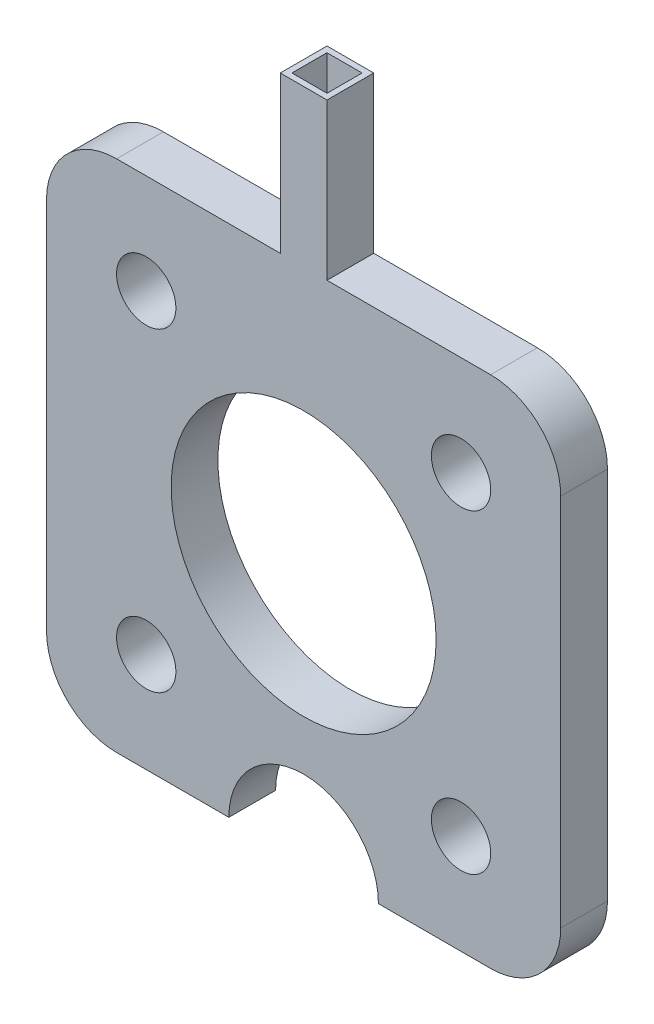
SolidWorks part; units mm, degrees
ref_plane "Front Plane" through (0, 0, 0) normal (0, 0, 1) x (1, 0, 0)
ref_plane "Top Plane" through (0, 0, 0) normal (0, 1, 0) x (1, 0, 0)
ref_plane "Right Plane" through (0, 0, 0) normal (1, 0, 0) x (0, 0, -1)
sketch "Sketch1" plane through (0, 0, 0) normal (0, 0, 1) x (1, 0, 0)
  line L1 (0, 0) -> (22, 0)
  line L2 (0, 0) -> (0, -22)
  line L3 (0, -22) -> (22, -22)
  line L4 (22, 0) -> (22, -22)
  dimension "D1" = 22
  dimension "D2" = 22
extrude "Boss-Extrude1" add sketch "Sketch1" along normal blind 2
fillet "Fillet1" radius 3 4 edges at (22, -22, 1) (0, -22, 1) (0, 0, 1) (22, 0, 1)
sketch "Sketch2" plane through (0, 0, 2) normal (0, 0, 1) x (1, 0, 0)
  line L0 (0, -3) -> (0, -19) construction
  line L1 (4.265, -4.265) -> (17.735, -4.265) construction
  line L2 (4.265, -4.265) -> (4.265, -17.735) construction
  line L3 (4.265, -17.735) -> (17.735, -17.735) construction
  line L4 (17.735, -4.265) -> (17.735, -17.735) construction
  line L5 (4.265, -4.265) -> (17.735, -17.735) construction
  line L6 (4.265, -17.735) -> (17.735, -4.265) construction
  line L7 (19, 0) -> (3, 0) construction
  circle A0 centre (4.265, -4.265) radius 1.27
  circle A1 centre (4.265, -17.735) radius 1.27
  circle A2 centre (17.735, -4.265) radius 1.27
  circle A3 centre (17.735, -17.735) radius 1.27
  point P0 (11, -11)
  dimension "D5" = 2.54
  dimension "D6" = 2.54
  dimension "D7" = 2.54
  dimension "D8" = 2.54
  dimension "D1" = 13.47
  dimension "D2" = 13.47
  dimension "D3" = 11
  dimension "D4" = 11
extrude "Cut-Extrude1" cut sketch "Sketch2" against normal through all
sketch "Sketch3" plane through (0, 0, 2) normal (0, 0, 1) x (1, 0, 0)
  line L0 (3, -22) -> (19, -22) construction
  line L1 (7.8, -22) -> (14.2, -22)
  arc A0 (7.8, -22) -> (14.2, -22) centre (11, -22) cw
  dimension "D1" = 3.2
extrude "Cut-Extrude2" cut sketch "Sketch3" against normal through all
sketch "Sketch4" plane through (0, 0, 2) normal (0, 0, 1) x (1, 0, 0)
  line L0 (0, -3) -> (0, -19) construction
  circle A0 centre (11, -11) radius 5.6689
  dimension "D1" = 11
extrude "Cut-Extrude3" cut sketch "Sketch4" against normal blind 10
sketch "Sketch5" plane through (0, 0, 0) normal (0, 1, 0) x (1, 0, 0)
  line L0 (19, -2) -> (3, -2) construction
  line L1 (10, 0) -> (12, 0)
  line L2 (10, 0) -> (10, -2)
  line L3 (10, -2) -> (12, -2)
  line L4 (12, 0) -> (12, -2)
  line L5 (10, 0) -> (12, -2) construction
  line L6 (10, -2) -> (12, 0) construction
  line L7 (3, 0) -> (3, -2) construction
  point P8 (11, -1)
  dimension "D1" = 8
  dimension "D2" = 2
  dimension "D3" = 2
extrude "Boss-Extrude2" add sketch "Sketch5" along normal blind 6.68
sketch "Sketch6" plane through (0, 6.68, 0) normal (0, 1, 0) x (1, 0, 0)
  line L0 (3, 0) -> (3, -2) construction
  line L1 (10.2487, -0.25) -> (11.7513, -0.25)
  line L2 (10.2487, -0.25) -> (10.2487, -1.75)
  line L3 (10.2487, -1.75) -> (11.7513, -1.75)
  line L4 (11.7513, -0.25) -> (11.7513, -1.75)
  line L5 (10.2487, -0.25) -> (11.7513, -1.75) construction
  line L6 (10.2487, -1.75) -> (11.7513, -0.25) construction
  line L7 (12, 0) -> (10, 0) construction
  point P0 (11, -1)
  point P7 (0, 0)
  dimension "D1" = 1.5
  dimension "D2" = 1.5026
  dimension "D3" = 8
  dimension "D4" = 1
extrude "Cut-Extrude4" cut sketch "Sketch6" against normal blind 6.8
